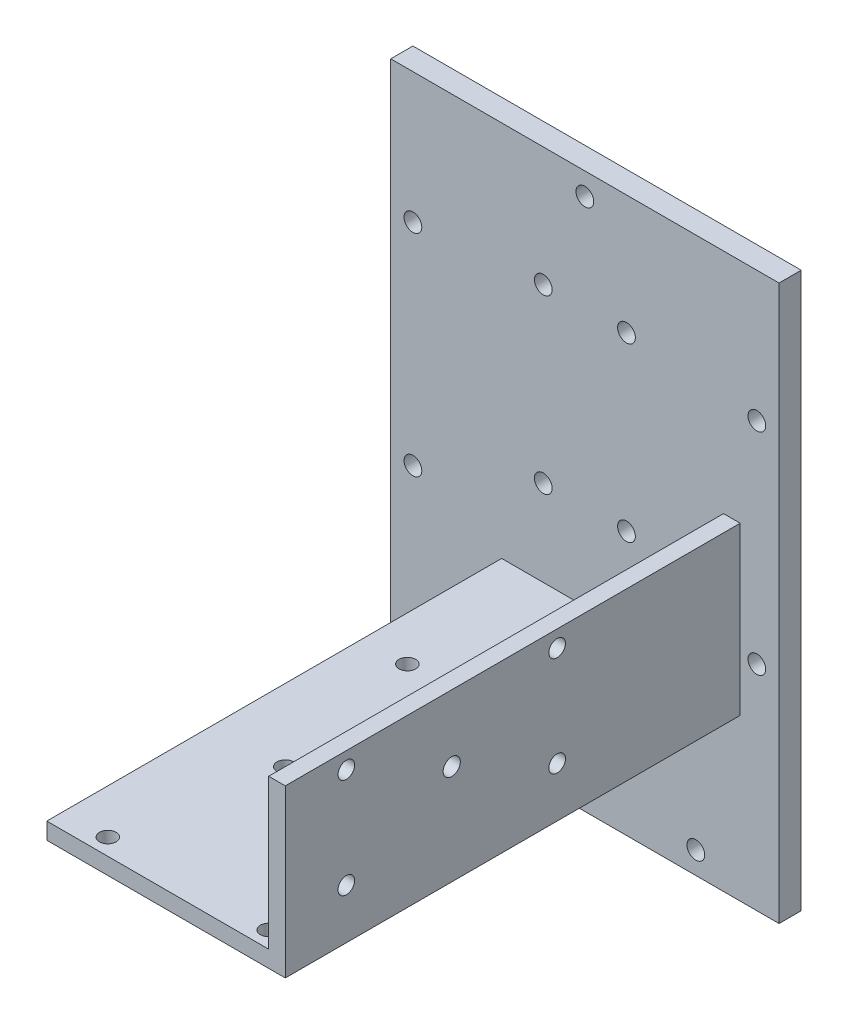
SolidWorks part; units mm, degrees
ref_plane "前视基准面" through (0, 0, 0) normal (0, 0, 1) x (1, 0, 0)
ref_plane "上视基准面" through (0, 0, 0) normal (0, 1, 0) x (1, 0, 0)
ref_plane "右视基准面" through (0, 0, 0) normal (1, 0, 0) x (0, 0, -1)
other "Configuration Table"
sketch "草图1" plane through (0, 0, 0) normal (0, 0, 1) x (1, 0, 0)
  line L0 (0, 0) -> (-16.666, 0) construction
  line L1 (-31.666, 50) -> (38.334, 50)
  line L2 (-31.666, 50) -> (-31.666, -50)
  line L3 (-31.666, -50) -> (38.334, -50)
  line L4 (38.334, 50) -> (38.334, -50)
  line L5 (-16.666, 46) -> (-16.666, -46) construction
  line L6 (-16.666, 46) -> (3.334, 46) construction
  line L7 (10.834, 28.5) -> (10.834, -2.5) construction
  line L8 (3.334, 46) -> (10.834, 46) construction
  line L9 (3.334, 46) -> (3.334, 28.5) construction
  line L10 (3.334, 28.5) -> (10.834, 28.5) construction
  line L11 (10.834, 46) -> (10.834, 28.5) construction
  line L12 (34.334, 26.5) -> (34.334, -11.5) construction
  line L13 (10.834, 28.5) -> (34.334, 28.5) construction
  line L14 (10.834, 28.5) -> (10.834, 26.5) construction
  line L15 (10.834, 26.5) -> (34.334, 26.5) construction
  line L16 (34.334, 28.5) -> (34.334, 26.5) construction
  circle A0 centre (34.334, 26.5) radius 1.6
  circle A1 centre (-16.666, -46) radius 1.6
  circle A2 centre (3.334, 46) radius 1.6
  circle A3 centre (10.834, 28.5) radius 1.6
  circle A4 centre (10.834, -2.5) radius 1.6
  circle A5 centre (34.334, -11.5) radius 1.6
  circle A6 centre (-27.666, 26.5) radius 1.6
  circle A7 centre (-4.166, 28.5) radius 1.6
  circle A8 centre (-4.166, -2.5) radius 1.6
  circle A9 centre (-27.666, -11.5) radius 1.6
  circle A10 centre (23.334, -46) radius 1.6
  point P0 (0, 0)
  point P11 (-16.666, 0)
  point P20 (-31.666, 0)
  dimension "D5" = 15
  dimension "D6" = 3.2
  dimension "D7" = 3.2
  dimension "D8" = 3.2
  dimension "D9" = 3.2
  dimension "D10" = 3.2
  dimension "D11" = 3.2
  dimension "D1" = 100
  dimension "D2" = 70
  dimension "D3" = 92
  dimension "D4" = 20
extrude "凸台-拉伸1" add sketch "草图1" along normal blind 4
sketch "草图2" plane through (0, 0, 4) normal (0, 0, 1) x (1, 0, 0)
  line L0 (3.334, -50) -> (3.334, 50) construction
  line L2 (-31.666, -50) -> (38.334, -50) construction
  line L3 (38.334, 50) -> (-31.666, 50) construction
  line L4 (3.334, -21) -> (28.334, -21)
  line L5 (3.334, -21) -> (-11.666, -21)
  line L7 (-11.666, -21) -> (28.334, -21)
  line L8 (-11.666, -21) -> (-11.666, -18)
  line L9 (-11.666, -18) -> (28.334, -18)
  line L10 (28.334, -21) -> (28.334, -18)
  circle A0 centre (-16.666, -46) radius 1.6 construction
  circle A1 centre (34.334, -11.5) radius 1.6 construction
  circle A2 centre (-16.666, -46) radius 1.6
  circle A3 centre (34.334, -11.5) radius 1.6
  dimension "D1" = 25
  dimension "D2" = 15
  dimension "D3" = 29
  dimension "D4" = 3
extrude "凸台-拉伸2" add sketch "草图2" along normal blind 82 contours L5 L0 L9 L8 | L0 L4 L10 L9
sketch "草图3" plane through (0, -21, 0) normal (0, -1, 0) x (1, 0, 0)
  line L5 (10.834, 89) -> (10.834, 23) construction
  line L6 (26.8584, 56) -> (-10.1904, 56) construction
  line L8 (-3.666, 83) -> (25.334, 83) construction
  line L9 (-3.666, 83) -> (-3.666, 29) construction
  line L10 (-3.666, 29) -> (25.334, 29) construction
  line L11 (25.334, 83) -> (25.334, 29) construction
  line L12 (-3.666, 83) -> (25.334, 29) construction
  line L13 (-3.666, 29) -> (25.334, 83) construction
  line L14 (28.334, 4) -> (-11.666, 4) construction
  line L19 (28.334, 86) -> (28.334, 4) construction
  line L20 (-11.666, 86) -> (-11.666, 4) construction
  line L21 (28.334, 86) -> (28.334, 4) construction
  line L22 (-11.666, 86) -> (-11.666, 4) construction
  circle A0 centre (-3.666, 83) radius 1.5
  circle A1 centre (25.334, 83) radius 1.5
  circle A2 centre (25.334, 29) radius 1.5
  circle A3 centre (-3.666, 29) radius 1.5
  circle A4 centre (8.334, 56) radius 7 construction
  circle A5 centre (8.334, 63) radius 1.5
  circle A6 centre (8.334, 56) radius 1.5392
  circle A13 centre (15.334, 56) radius 1.5
  circle A14 centre (8.334, 49) radius 1.5
  circle A15 centre (1.334, 56) radius 1.5
  point P11 (10.834, 56)
  point P30 (13.334, 70)
  point P37 (8.334, 56)
  dimension "D3" = 3
  dimension "D4" = 14
  dimension "D5" = 3
  dimension "D7" = 4
  dimension "D9" = 7
  dimension "D1" = 29
  dimension "D2" = 54
  dimension "D6" = 25
extrude "切除-拉伸1" cut sketch "草图3" against normal blind 8
sketch "草图5" plane through (0, 0, 4) normal (0, 0, 1) x (1, 0, 0)
  line L0 (-11.666, -18) -> (28.334, -18) construction
  line L1 (-11.666, -18) -> (28.334, -18)
  line L2 (8.334, -18) -> (8.334, -5.462)
ref_plane "基准面1" through (8.334, 0, 0) normal (1, 0, 0) x (0, 1, 0)
sketch "草图6" plane through (8.334, 0, 0) normal (1, 0, 0) x (0, 1, 0)
  line L1 (-21, 86) -> (-21, 4) construction
  line L4 (-21, 4) -> (-18, 4) construction
  line L5 (-21, 4) -> (-18, 4)
  line L6 (-19.5, 4) -> (-19.5, 59.4681) construction
  line L7 (-21, 44.6174) -> (-36.5708, 4)
  line L8 (-21, 4) -> (-36.5708, 4)
  line L9 (-21, 44.6174) -> (-21, 4)
  line L10 (-50, 4) -> (50, 4) construction
extrude "凸台-拉伸3" add sketch "草图6" along normal mid plane 4 contours L7 L8 L9
sketch "草图7" plane through (0, 0, 4) normal (0, 0, 1) x (1, 0, 0)
  line L0 (-11.666, -18) -> (28.334, -18) construction
  line L1 (-11.666, -18) -> (28.334, -18)
  line L2 (28.334, -18) -> (28.334, 9)
  line L3 (28.334, 9) -> (31.334, 9)
  line L4 (31.334, 9) -> (31.334, -21)
  line L6 (31.334, -21) -> (28.334, -21)
  line L7 (28.334, -21) -> (28.334, -18)
  circle M4 centre (34.334, -11.5) radius 1.6
  line M24 (28.334, -18) -> (28.334, -21)
  dimension "D1" = 27
  dimension "D2" = 3
extrude "凸台-拉伸5" add sketch "草图7" along normal blind 82 contours L6 L4 L3 L2 M24 M4
sketch "草图10" plane through (31.334, 0, 0) normal (1, 0, 0) x (0, 0, -1)
  line L5 (-86, 9) -> (-78.5, 9)
  line L6 (-86, 9) -> (-4, 9) construction
  line L7 (-78.5, -3) -> (-33.5, -3) construction
  line L8 (-78.5, 9) -> (-33.5, 9) construction
  line L9 (-78.5, 9) -> (-78.5, -15) construction
  line L10 (-78.5, -15) -> (-33.5, -15) construction
  line L11 (-33.5, 9) -> (-33.5, -15) construction
  line L12 (-56, -12) -> (-56, 6) construction
  line L17 (-75, -12) -> (-37, 6) construction
  line L18 (-75, 6) -> (-37, -12) construction
  circle A0 centre (-75, -12) radius 1.5
  circle A1 centre (-56, -3) radius 1.55
  circle A2 centre (-75, 6) radius 1.5
  circle A3 centre (-37, 6) radius 1.5
  circle A4 centre (-37, -12) radius 1.5
  point P11 (-56, -3)
  point P23 (-56, -3)
  dimension "D5" = 3.1
  dimension "D6" = 3
  dimension "D1" = 24
  dimension "D2" = 45
  dimension "D3" = 18
  dimension "D4" = 38
extrude "切除-拉伸2" cut sketch "草图10" against normal through all contours A4 | A3 | A0 | A2 | A1
